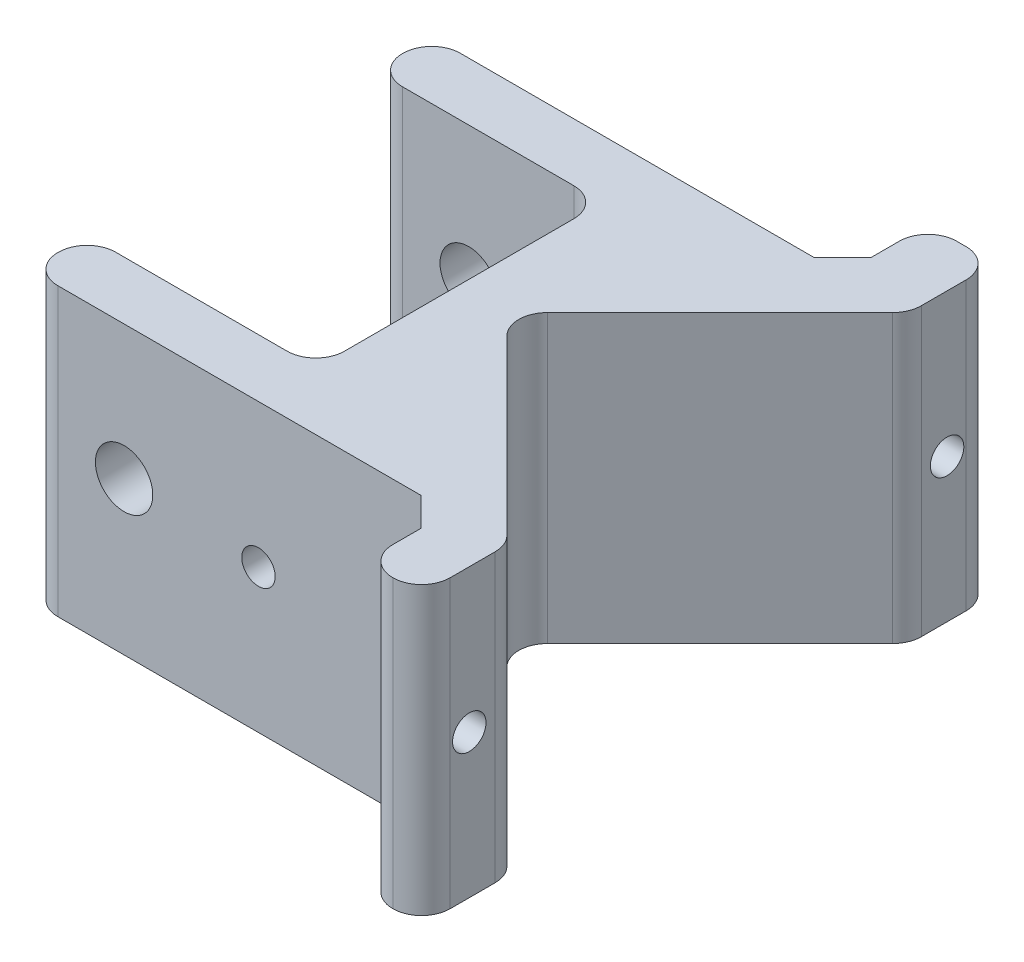
SolidWorks part; units mm, degrees
ref_plane "Front Plane" through (0, 0, 0) normal (0, 0, 1) x (1, 0, 0)
ref_plane "Top Plane" through (0, 0, 0) normal (0, 1, 0) x (1, 0, 0)
ref_plane "Right Plane" through (0, 0, 0) normal (1, 0, 0) x (0, 0, -1)
sketch "Sketch1" plane through (0, 0, 0) normal (0, 1, 0) x (1, 0, 0)
  line L0 (-65, 21.0624) -> (-65, -21.0624)
  line L1 (0, -36.0624) -> (36.0624, 0) construction
  line L2 (0, -36.0624) -> (-36.0624, 0) construction
  line L3 (-36.0624, 0) -> (0, 36.0624) construction
  line L4 (36.0624, 0) -> (0, 36.0624) construction
  line L5 (0, -36.0624) -> (0, 36.0624) construction
  line L6 (-36.0624, 0) -> (36.0624, 0) construction
  line L7 (-21.0058, -30) -> (-15, -30)
  line L8 (-15, -30) -> (-15, -21.0624)
  line L9 (-15, -21.0624) -> (-36.0624, 0)
  line L10 (-36.0624, 0) -> (-15, 21.0624)
  line L11 (-15, 21.0624) -> (-15, 30)
  line L12 (-15, 30) -> (-22, 30)
  line L13 (-21.0058, -21.0624) -> (-65, -21.0624)
  line L14 (-21.0058, -21.0624) -> (-21.0058, -30)
  line L15 (-65, 21.0624) -> (-22, 21.0624)
  line L16 (-22, 21.0624) -> (-22, 30)
  point P0 (0, 0)
  dimension "D1" = 51
  dimension "D2" = 51
  dimension "D3" = 30
  dimension "D4" = 65
  dimension "D5" = 7
  dimension "D6" = 30
extrude "Boss-Extrude1" add sketch "Sketch1" along normal blind 30
sketch "Sketch2" plane through (0, 30, 0) normal (0, 1, 0) x (1, 0, 0)
  line L1 (-71.0624, 15) -> (-41.0624, 15)
  line L2 (-71.0624, 15) -> (-71.0624, -15)
  line L3 (-71.0624, -15) -> (-41.0624, -15)
  line L4 (-41.0624, 15) -> (-41.0624, -15)
  line L5 (-71.0624, 15) -> (-41.0624, -15) construction
  line L6 (-71.0624, -15) -> (-41.0624, 15) construction
  point P0 (-56.0624, 0)
  dimension "D1" = 30
  dimension "D2" = 30
  dimension "D3" = 20
extrude "Cut-Extrude1" cut sketch "Sketch2" against normal blind 30
chamfer "Chamfer1" distance 3 angle 45 2 edges at (-21.0058, 15, 21.0624) (-22, 15, -21.0624)
fillet "Fillet1" radius 3 5 edges at (-36.0624, 15, 0) (-41.0624, 15, 15) (-41.0624, 15, -15) (-15, 15, 21.0624) (-15, 15, -21.0624)
fillet "Fillet2" radius 3 8 edges at (-65, 15, 15) (-65, 15, -21.0624) (-65, 15, -15) (-65, 15, 21.0624) (-21.0058, 15, 30) (-15, 15, 30) (-22, 15, -30) (-15, 15, -30)
sketch "Sketch3" plane through (-22, 0, 0) normal (-1, 0, 0) x (0, 0, 1)
  circle A0 centre (-25, 15) radius 1.75
  circle A1 centre (25, 15) radius 1.75
  dimension "D1" = 3.5
  dimension "D2" = 3.5
  dimension "D3" = 15
  dimension "D4" = 25
  dimension "D5" = 25
extrude "Cut-Extrude2" cut sketch "Sketch3" against normal blind 30 and the other way blind 30
sketch "Sketch4" plane through (0, 0, -15) normal (0, 0, 1) x (1, 0, 0)
  line L0 (-41.0624, 30) -> (-41.0624, 0) construction
  circle A0 centre (-55.0624, 15.9838) radius 3
  dimension "D1" = 6
  dimension "D2" = 14
extrude "Cut-Extrude3" cut sketch "Sketch4" against normal blind 30 and the other way blind 50
sketch "Sketch5" plane through (0, 0, -21.0624) normal (0, 0, -1) x (-1, 0, 0)
  circle A0 centre (41, 15) radius 1.75
  dimension "D1" = 3.5
  dimension "D2" = 15
  dimension "D3" = 41
extrude "Cut-Extrude4" cut sketch "Sketch5" against normal through all both and the other way through all
sketch "Sketch6" plane through (0, 0, 0) normal (0, 1, 0) x (1, 0, 0)
  line L0 (-15, 15) -> (15, 15)
  line L2 (15, 15) -> (15, -15)
  line L3 (15, -15) -> (-15, -15)
  line L4 (-15, 23.9288) -> (-37.2978, 2.8035)
  line L7 (-15, 23.9288) -> (-15, 15)
  line L8 (-15, 22.3051) -> (-15, 27) construction
  line L9 (-15, -24.6525) -> (-15, -15)
  line L10 (-15, -27) -> (-15, -22.3051) construction
  line L11 (-37.2978, 2.8035) -> (-37.2978, -1.4157)
  line L12 (-37.2978, -1.4157) -> (-15, -24.6525)
  dimension "D1" = 15
  dimension "D2" = 15
  dimension "D3" = 15
